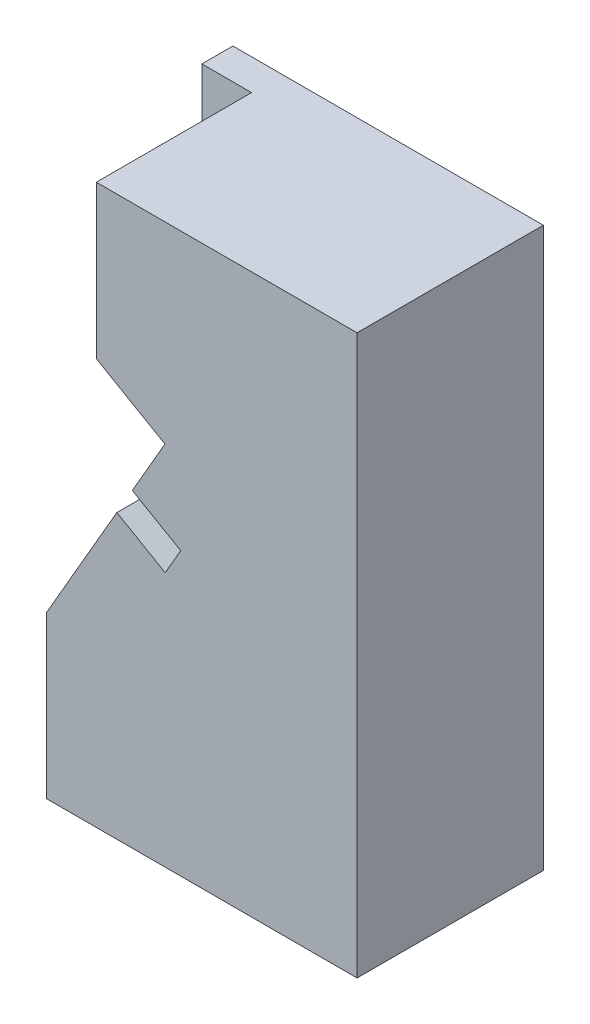
SolidWorks part; units mm, degrees
ref_plane "Front" through (0, 0, 0) normal (0, 0, 1) x (1, 0, 0)
ref_plane "Top" through (0, 0, 0) normal (0, 1, 0) x (1, 0, 0)
ref_plane "Right" through (0, 0, 0) normal (1, 0, 0) x (0, 0, -1)
sketch "Sketch1" plane through (0, 0, 0) normal (0, 1, 0) x (1, 0, 0)
  line L1 (-12.5, 7.5) -> (12.5, 7.5)
  line L2 (-12.5, 7.5) -> (-12.5, -7.5)
  line L3 (-12.5, -7.5) -> (12.5, -7.5)
  line L4 (12.5, 7.5) -> (12.5, -7.5)
  line L5 (-12.5, 7.5) -> (12.5, -7.5) construction
  line L6 (-12.5, -7.5) -> (12.5, 7.5) construction
  point P0 (0, 0)
  dimension "D1" = 25
  dimension "D2" = 15
extrude "Boss-Extrude2" add sketch "Sketch1" along normal mid plane 45 contours L1 L4 L3 L2
sketch "Sketch2" plane through (0, 0, 7.5) normal (0, 0, 1) x (1, 0, 0)
  line L0 (-12.5, 22.5) -> (-12.5, -22.5) construction
  line L1 (-12.5, 21.5) -> (12.5, 21.5)
  line L2 (-12.5, 21.5) -> (-12.5, -2.5)
  line L3 (-12.5, -2.5) -> (12.5, -2.5)
  line L4 (12.5, 21.5) -> (12.5, -2.5)
  line L5 (12.5, 22.5) -> (12.5, -22.5) construction
  line L6 (-12.5, -22.5) -> (12.5, -22.5) construction
  dimension "D1" = 20
  dimension "D2" = 24
extrude "Cut-Extrude1" [suppressed] cut sketch "Sketch2" against normal blind 12.5
sketch "Sketch3" [suppressed] plane through (0, 0, 0) normal (0, 0, 1) x (1, 0, 0)
  line L0 (-3.75, 6.5) -> (-3.75, 1.25)
  line L1 (12.5, 6.5) -> (-12.5, 6.5) construction
  line L2 (-3.75, 1.25) -> (0.75, 1.25)
  line L3 (0.75, 1.25) -> (0.75, -1.25)
  line L4 (0.75, -1.25) -> (-3.75, -1.25)
  line L5 (-3.75, -1.25) -> (-3.75, -17.5)
  line L6 (-12.5, -17.5) -> (12.5, -17.5) construction
  line L7 (-3.75, -17.5) -> (12.5, -17.5)
  line L8 (12.5, -17.5) -> (12.5, 6.5)
  line L9 (12.5, 6.5) -> (-3.75, 6.5)
  dimension "D1" = 5.25
  dimension "D2" = 2.5
  dimension "D3" = 16.25
  dimension "D4" = 4.5
extrude "Boss-Extrude3" [suppressed] add sketch "Sketch3" along normal blind 12.5
sketch "Sketch5" plane through (0, 0, 7.5) normal (0, 0, 1) x (1, 0, 0)
  line L0 (-8.5, 10.1906) -> (-2.9737, 7)
  line L1 (-12.5, 22.5) -> (-12.5, -22.5) construction
  line L2 (-2.9737, 7) -> (-5.5987, 2.4534)
  line L3 (-5.5987, 2.4534) -> (-1.7016, 0.2034)
  line L4 (-1.7016, 0.2034) -> (-2.9516, -1.9617)
  line L5 (-2.9516, -1.9617) -> (-6.8487, 0.2883)
  line L6 (-6.8487, 0.2883) -> (-12.5, -9.5)
  line L7 (-12.5, 24.7906) -> (-12.5, -9.5)
  line L8 (-12.5, -22.5) -> (12.5, -22.5) construction
  line L9 (-12.5, 24.7906) -> (-8.5, 24.7906)
  line L10 (-8.5, 24.7906) -> (-8.5, 10.1906)
  dimension "D1" = 5.25
  dimension "D2" = 30
  dimension "D3" = 4.5
  dimension "D4" = 2.5
  dimension "D5" = 34.2906
  dimension "D6" = 13
  dimension "D7" = 4
  dimension "D8" = 14.6
extrude "Cut-Extrude2" cut sketch "Sketch5" against normal blind 12.5
